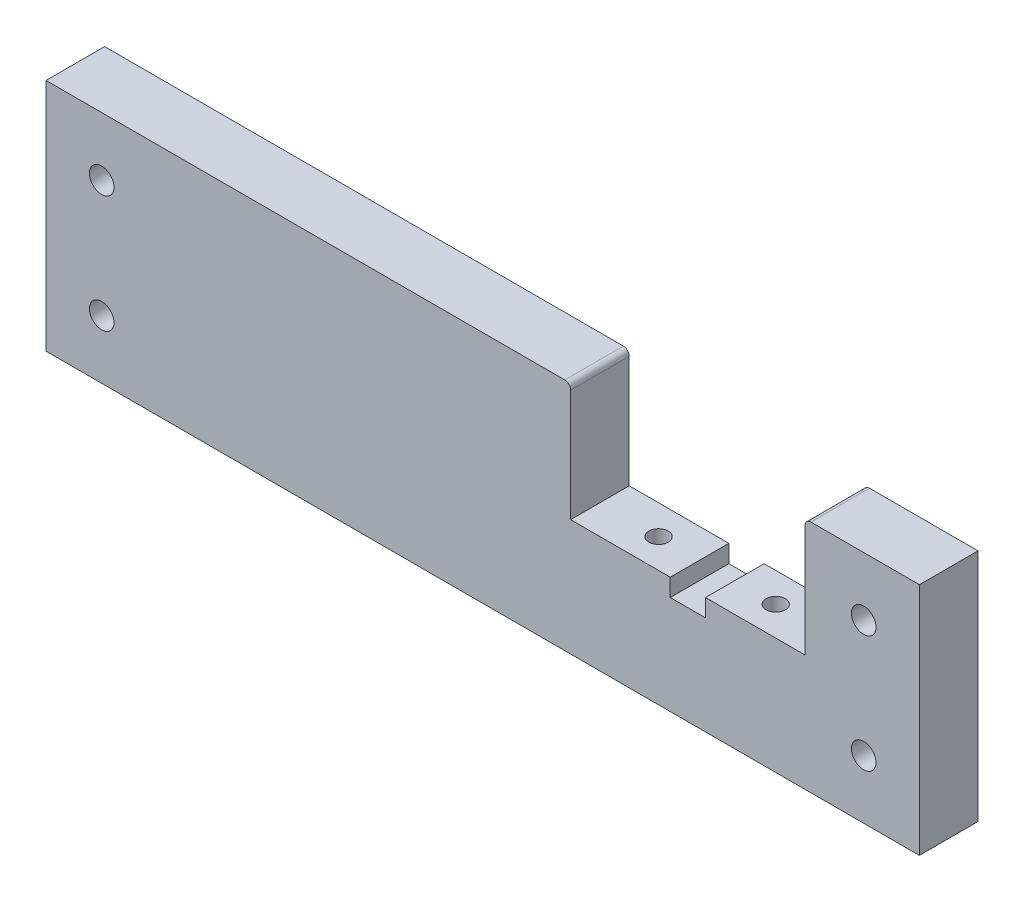
SolidWorks part; units mm, degrees
material "6061-T6 (SS)"
ref_plane "Front Plane" through (0, 0, 0) normal (0, 0, 1) x (1, 0, 0)
ref_plane "Top Plane" through (0, 0, 0) normal (0, 1, 0) x (1, 0, 0)
ref_plane "Right Plane" through (0, 0, 0) normal (1, 0, 0) x (0, 0, -1)
sketch "Sketch1" plane through (0, 0, 0) normal (0, 0, 1) x (1, 0, 0)
  line L0 (-65, 30) -> (-65, 10) construction
  line L1 (-74.5, 40) -> (74.5, 40)
  line L2 (-74.5, 40) -> (-74.5, 0)
  line L3 (-74.5, 0) -> (74.5, 0)
  line L4 (74.5, 40) -> (74.5, 0)
  line L5 (31.995, 22.86) -> (38.005, 22.86)
  line L6 (31.995, 22.86) -> (31.995, 16.85)
  line L7 (31.995, 16.85) -> (38.005, 16.85)
  line L8 (38.005, 22.86) -> (38.005, 16.85)
  line L9 (32, 22.855) -> (38, 22.855) construction
  line L10 (32, 22.855) -> (32, 16.855) construction
  line L11 (32, 16.855) -> (38, 16.855) construction
  line L12 (38, 22.855) -> (38, 16.855) construction
  line L13 (0, 0) -> (0, 40) construction
  line L14 (38.005, 19.855) -> (55, 19.855)
  line L15 (31.995, 19.855) -> (15, 19.855)
  line L16 (15, 19.855) -> (15, 40)
  line L17 (55, 19.855) -> (55, 40)
  circle A0 centre (-65, 30) radius 2.5 construction
  circle A1 centre (-65, 10) radius 2.5 construction
  circle A2 centre (65, 10) radius 2.5 construction
  circle A3 centre (65, 30) radius 2.5 construction
  point P10 (0, 0)
  point P14 (35, 22.855)
  point P15 (35, 22.86)
  point P16 (32, 19.855)
  point P17 (31.995, 19.855)
  point P34 (38.005, 19.855)
  dimension "D8" = 5
  dimension "D1" = 6.01
  dimension "D2" = 149
  dimension "D3" = 40
  dimension "D4" = 16.85
  dimension "D5" = 32
  dimension "D6" = 6
  dimension "D7" = 20
  dimension "D9" = 10
  dimension "D10" = 65
  dimension "D11" = 40
extrude "Boss-Extrude1" add sketch "Sketch1" against normal blind 10 contours L17 L14 L8 L7 L6 L15 L16 L1 L2 L3 L4
sketch "Sketch4" plane through (0, 0, 0) normal (0, -1, 0) x (1, 0, 0)
  line L0 (-60, -5) -> (60, -5) construction
  line L2 (-74.5, 0) -> (74.5, 0)
  line L3 (-74.5, 0) -> (-74.5, -10)
  line L4 (-74.5, -10) -> (74.5, -10)
  line L5 (74.5, 0) -> (74.5, -10)
  circle A0 centre (0, -5) radius 2.5 construction
  circle A1 centre (60, -5) radius 2.5 construction
  circle A2 centre (-60, -5) radius 2.5 construction
  point P6 (0, -5)
  point P14 (74.5, -5)
  dimension "D1" = 5
  dimension "D2" = 120
sketch "Sketch8" plane through (0, 19.855, 0) normal (0, 1, 0) x (1, 0, 0)
  line L0 (31.995, 0) -> (15, 0) construction
  line L1 (15, 0) -> (15, 10) construction
  line L2 (15, 10) -> (31.995, 10) construction
  line L3 (31.995, 10) -> (31.995, 0) construction
  line L4 (55, 0) -> (38.005, 0) construction
  line L5 (38.005, 0) -> (38.005, 10) construction
  line L6 (38.005, 10) -> (55, 10) construction
  line L7 (55, 10) -> (55, 0) construction
  line L8 (31.995, 0) -> (15, 0) construction
  line L9 (15, 0) -> (15, 10) construction
  line L10 (15, 10) -> (31.995, 10) construction
  line L11 (31.995, 10) -> (31.995, 0) construction
  line L12 (55, 0) -> (38.005, 0) construction
  line L13 (38.005, 0) -> (38.005, 10) construction
  line L14 (38.005, 10) -> (55, 10) construction
  line L15 (55, 10) -> (55, 0) construction
  line L16 (25, 5) -> (45, 5)
  line L17 (31.995, 10) -> (38.005, 10)
  circle A0 centre (45, 5) radius 2 construction
  circle A1 centre (25, 5) radius 2 construction
  point P4 (35, 5)
  point P5 (35, 10)
  point P10 (31.995, 5)
  dimension "D1" = 4
  dimension "D2" = 20
  dimension "D4" = 10
  dimension "D3" = 10
hole_wizard "Tap Drill for M4x0.7 Tap1" positions "3DSketch3" profile "Sketch9" hole size "M4x0.7" standard "ANSI Metric"
sketch3d "3DSketch3"
  point P0 (25, 19.855, -5)
  point P2 (45, 19.855, -5)
sketch "Sketch9" plane through (25, 19.855, -5) normal (1, 0, 0) x (0, 0, 1)
  line L0 (0, 0) -> (0, 5.9914)
  line L1 (0, 5.9914) -> (1.65, 5)
  line L2 (1.65, 5) -> (1.65, 0)
  line L5 (1.65, 0) -> (0, 0)
  line L10 (0, 5.9914) -> (-1.65, 5) construction
  line L11 (0, -6.35) -> (0, 107.95) construction
  dimension "Hole Dia." = 3.3
  dimension "Hole Depth" = 5
  dimension "Drill Angle" = 118
hole_wizard "Tap Drill for M5x0.8 Tap3" positions "3DSketch4" profile "Sketch10" hole size "M5x0.8" standard "ANSI Metric" end condition up to next
sketch3d "3DSketch4"
  point P0 (-65, 30, 0)
  point P2 (-65, 10, 0)
  point P4 (65, 10, 0)
  point P6 (65, 30, 0)
sketch "Sketch10" plane through (-65, 30, 0) normal (1, 0, 0) x (0, -1, 0)
  line L0 (0, 0) -> (0, 10)
  line L1 (0, 10) -> (2.1, 10)
  line L2 (2.1, 10) -> (2.1, 0)
  line L5 (2.1, 0) -> (0, 0)
  line L11 (0, -6.35) -> (0, 107.95) construction
  dimension "Thru Hole Dia." = 4.2
  dimension "Thru Hole Depth" = 10
hole_wizard "Tap Drill for M5x0.8 Tap2" positions "3DSketch2" profile "Sketch5" hole size "M5x0.8" standard "ANSI Metric"
sketch3d "3DSketch2"
  point P0 (-60, 0, -5)
  point P2 (0, 0, -5)
  point P4 (60, 0, -5)
sketch "Sketch5" plane through (-60, 0, -5) normal (1, 0, 0) x (0, 0, -1)
  line L0 (0, 0) -> (0, 8.2618)
  line L1 (0, 8.2618) -> (2.1, 7)
  line L2 (2.1, 7) -> (2.1, 0)
  line L5 (2.1, 0) -> (0, 0)
  line L10 (0, 8.2618) -> (-2.1, 7) construction
  line L11 (0, -6.35) -> (0, 107.95) construction
  dimension "Hole Dia." = 4.2
  dimension "Hole Depth" = 7
  dimension "Drill Angle" = 118
fillet "Fillet1" radius 1 2 edges at (15, 40, -5) (55, 40, -5)
